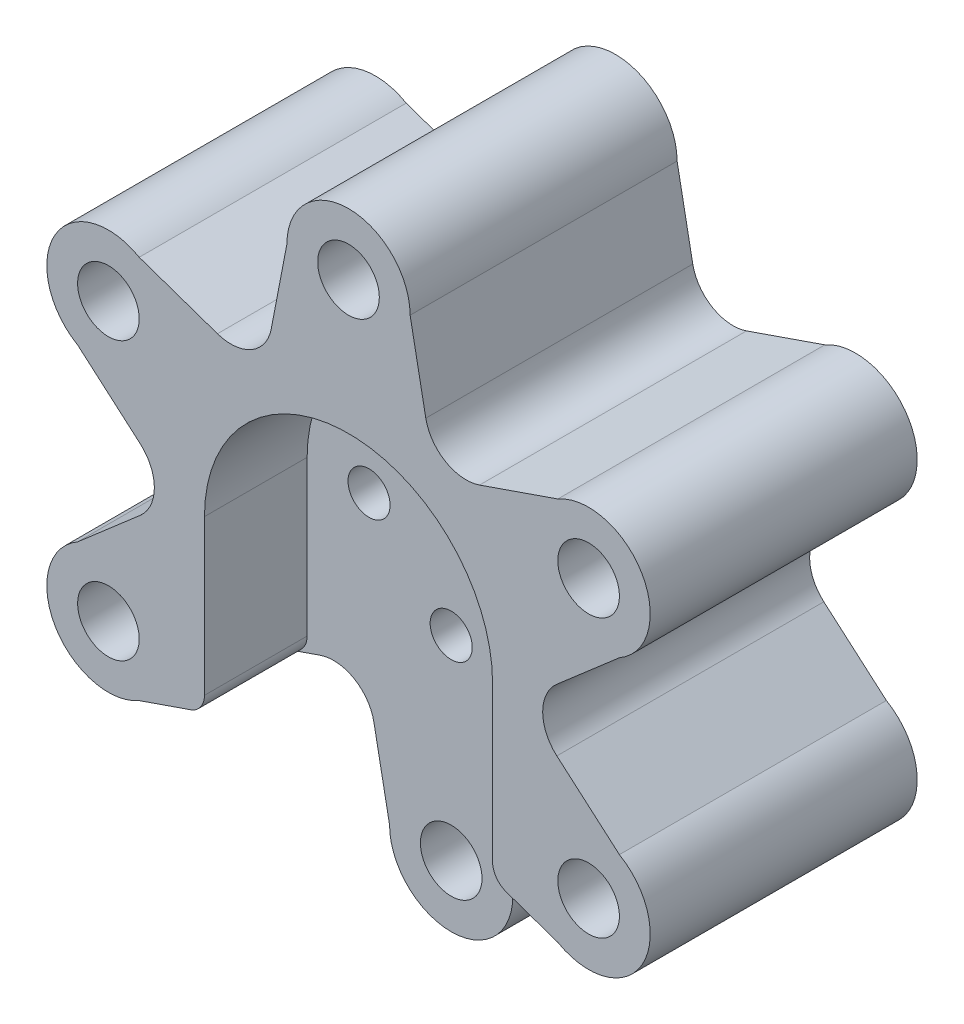
SolidWorks part; units mm, degrees
material "6061 合金"
ref_plane "前视基准面" through (0, 0, 0) normal (0, 0, 1) x (1, 0, 0)
ref_plane "上视基准面" through (0, 0, 0) normal (0, 1, 0) x (1, 0, 0)
ref_plane "右视基准面" through (0, 0, 0) normal (1, 0, 0) x (0, 0, -1)
sketch "草图2" plane through (0, 0, 0) normal (0, 0, 1) x (1, 0, 0)
  line L0 (0, 0) -> (0, 30) construction
  line L1 (-7.5425, 32.6667) -> (-16.9706, 6)
  line L2 (7.5425, 32.6667) -> (16.9706, 6)
  line L3 (-11.6913, -6.75) -> (0, 13.5) construction
  line L4 (0, 13.5) -> (11.6913, -6.75) construction
  line L5 (11.6913, -6.75) -> (-11.6913, -6.75) construction
  line L6 (0, 19.5) -> (-16.8875, -9.75) construction
  line L7 (-16.8875, -9.75) -> (16.8875, -9.75) construction
  line L8 (16.8875, -9.75) -> (0, 19.5) construction
  circle A0 centre (0, 0) radius 13.5 construction
  circle A1 centre (0, 13.5) radius 1.5
  circle A2 centre (11.6913, -6.75) radius 1.5
  circle A3 centre (-11.6913, -6.75) radius 1.5
  circle A4 centre (0, 0) radius 18 construction
  circle A5 centre (0, 30) radius 8
  circle A6 centre (0, 30) radius 2.5
  circle A7 centre (0, 0) radius 10.5
  circle A8 centre (0, -13.5) radius 1.5
  circle A9 centre (-11.6913, 6.75) radius 1.5
  circle A10 centre (11.6913, 6.75) radius 1.5
  circle A11 centre (0, 0) radius 18
  point P12 (0, 0)
  point P31 (0, 0)
  dimension "D1" = 27
  dimension "D2" = 3
  dimension "D4" = 36
  dimension "D6" = 16
  dimension "D8" = 5
  dimension "D10" = 3
  dimension "D12" = 36
  dimension "D13" = 3
  dimension "D5" = 30
  dimension "D7" = 3
  dimension "D9" = 3
  dimension "D3" = 3
  dimension "D11" = 3
extrude "凸台-拉伸1" add sketch "草图2" along normal blind 8 contours A11 A1 A2 A3 A7 A8 A9 A10
sketch "草图6" plane through (0, 0, 8) normal (0, 0, 1) x (1, 0, 0)
  circle A0 centre (0, 0) radius 10.5 construction
  circle A1 centre (0, 0) radius 10.5
extrude "凸台-拉伸2" add sketch "草图6" against normal blind 4
sketch "草图7" plane through (0, 0, 8) normal (0, 0, 1) x (1, 0, 0)
  line L0 (0, 0) -> (0, 20) construction
  line L1 (-7.5, 0) -> (-7.5, 20)
  line L2 (7.5, 0) -> (7.5, 20)
  arc A1 (-7.5, 0) -> (7.5, 0) centre (0, 0) ccw
  arc A2 (7.5, 20) -> (-7.5, 20) centre (0, 20) ccw
  circle A3 centre (0, 20) radius 3
  circle A4 centre (0, 0) radius 4 construction
  circle A5 centre (0, 4) radius 1.5
  circle A6 centre (4, 0) radius 1.5
  circle A7 centre (0, -4) radius 1.5
  circle A8 centre (-4, 0) radius 1.5
  point P3 (0, 10)
  point P24 (0, 0)
  dimension "D1" = 20
  dimension "D2" = 7.5
  dimension "D3" = 6
  dimension "D4" = 3
  dimension "D6" = 8
  dimension "D5" = 4
extrude "凸台-拉伸3" add sketch "草图7" along normal blind 4 separate body
sketch "草图9" plane through (0, 0, 8) normal (0, 0, 1) x (1, 0, 0)
  circle A0 centre (0, 4) radius 1.025
  circle A1 centre (-4, 0) radius 1.025
  circle A2 centre (0, -4) radius 1.025
  circle A3 centre (4, 0) radius 1.025
  dimension "D1" = 2.05
extrude "切除-拉伸2" cut sketch "草图9" against normal blind 4
sketch "草图11" plane through (0, 0, 12) normal (0, 0, 1) x (1, 0, 0)
  line L0 (-6.5, 20) -> (-7.5, 18.2679)
  line L1 (-7.5, 20) -> (-7.5, 0) construction
  line L2 (0, 20) -> (0, 0) construction
  line L3 (6.5, 20) -> (7.5, 18.2679)
  circle A0 centre (0, 20) radius 6.5
  line M7 (7.5, 0) -> (7.5, 20)
  arc M8 (7.5, 20) -> (-7.5, 20) centre (0, 20) ccw
  line M9 (-7.5, 20) -> (-7.5, 0)
  dimension "D1" = 13
  dimension "D2" = 30
extrude "切除-拉伸3" cut sketch "草图11" against normal blind 13 contours A0 L3 L0 M7 M8 M9
sketch "草图12" plane through (0, 0, 12) normal (0, 0, 1) x (1, 0, 0)
  line L0 (0, 20) -> (0, 0) construction
  line L1 (0, 12) -> (0, 10) construction
  line L2 (2.8, 12) -> (2.8, 10)
  line L3 (-2.8, 12) -> (-2.8, 10)
  arc A0 (2.8, 12) -> (-2.8, 12) centre (0, 12) ccw
  arc A1 (-2.8, 10) -> (2.8, 10) centre (0, 10) ccw
  point P6 (0, 11)
  dimension "D1" = 2.8
  dimension "D2" = 8
  dimension "D3" = 10
extrude "切除-拉伸4" cut sketch "草图12" against normal blind 23
sketch "草图13" plane through (0, 0, 8) normal (0, 0, 1) x (1, 0, 0)
  line L0 (0, 0) -> (0, 13.5) construction
  line L1 (-3, 13.5) -> (-4.2, 7.2746)
  line L2 (3, 13.5) -> (4.2, 7.2746)
  line L3 (10.1913, 9.3481) -> (4.2, 7.2746)
  line L4 (13.1913, 4.1519) -> (8.4, 0)
  line L5 (13.1913, -4.1519) -> (8.4, 0)
  line L6 (10.1913, -9.3481) -> (4.2, -7.2746)
  line L7 (3, -13.5) -> (4.2, -7.2746)
  line L8 (-3, -13.5) -> (-4.2, -7.2746)
  line L9 (-10.1913, -9.3481) -> (-4.2, -7.2746)
  line L10 (-13.1913, -4.1519) -> (-8.4, 0)
  line L11 (-13.1913, 4.1519) -> (-8.4, 0)
  line L12 (-10.1913, 9.3481) -> (-4.2, 7.2746)
  circle A0 centre (0, 13.5) radius 3
  circle A1 centre (11.6913, 6.75) radius 3
  circle A2 centre (11.6913, -6.75) radius 3
  circle A3 centre (0, -13.5) radius 3
  circle A4 centre (-11.6913, -6.75) radius 3
  circle A5 centre (-11.6913, 6.75) radius 3
  point P18 (0, 0)
  point P43 (0, 0)
  circle M13 centre (0, 0) radius 18
  dimension "D1" = 6
  dimension "D3" = 6
  dimension "D4" = 8.4
  dimension "D2" = 6
extrude "切除-拉伸5" cut sketch "草图13" against normal blind 8 contours A5 L12 L1 A0 L2 L3 A1 L4 L5 A2 L6 L7 A3 L8 L9 A4 L10 L11 M13
fillet "圆角6" radius 2 18 edges at (-8.4, 0, 6) (-10.3615, -1.6997, 2) (-6.6528, -8.1235, 2) (-4.2, -7.2746, 6) (-3.7087, -9.8232, 2) (3.7087, -9.8232, 2) (4.2, -7.2746, 6) (6.6528, -8.1235, 2) (10.3615, -1.6997, 2) (8.4, 0, 6) (10.3615, 1.6997, 2) (6.6528, 8.1235, 2) (4.2, 7.2746, 6) (3.7087, 9.8232, 2) (-4.2, 7.2746, 6) (-6.6528, 8.1235, 2) (-10.3615, 1.6997, 2) (-3.7087, 9.8232, 2)
sketch "草图15" plane through (0, 0, 12) normal (0, 0, 1) x (1, 0, 0)
  arc A1 (2.6872, 12.7869) -> (-2.6872, 12.7869) centre (0, 20) ccw
  arc A2 (2.8, 12) -> (-2.8, 12) centre (0, 12) ccw construction
  arc A3 (2.6872, 12.7869) -> (-2.6872, 12.7869) centre (0, 12) ccw
hole_wizard "M4 六角凹锥坑螺钉的锥形沉头孔2" positions "3D草图2" profile "草图20" countersink size "M4" standard "ISO"
sketch3d "3D草图2"
  circle A0 centre (0, 20, 8) radius 3 construction
  point P0 (0, 20, 8)
  point P5 (0, 20, 11)
sketch "草图20" plane through (0, 20, 8) normal (1, 0, 0) x (0, 1, 0)
  line L0 (0, 0) -> (0, 11.3519)
  line L1 (0, 11.3519) -> (2.25, 10)
  line L2 (2.25, 10) -> (2.25, 2.23)
  line L3 (2.25, 2.23) -> (4.48, 0)
  line L5 (4.48, 0) -> (0, 0)
  line L6 (-2.25, 2.23) -> (-4.48, 0) construction
  line L10 (0, 11.3519) -> (-2.25, 10) construction
  line L11 (0, -6.35) -> (0, 107.95) construction
  dimension "孔直径" = 4.5
  dimension "孔深度" = 10
  dimension "近端锥形沉头孔直径" = 8.96
  dimension "近端锥形沉头孔角度" = 90
  dimension "导头角度" = 118
fillet "圆角7" radius 2 4 edges at (-7.5, 18.2679, 10) (7.5, 18.2679, 10) (-6.5, 20, 10) (6.5, 20, 10)
sketch "草图21" plane through (0, 0, 0) normal (0, 0, -1) x (-1, 0, 0)
  circle A0 centre (0, 0) radius 16.5
  dimension "D1" = 33
sketch "草图22" plane through (0, 0, 12) normal (0, 0, 1) x (1, 0, 0)
  circle A0 centre (0, 0) radius 26.5
  dimension "D1" = 53
extrude "切除-拉伸7" cut sketch "草图22" against normal blind 4
sketch "草图23" plane through (0, 0, 8) normal (0, 0, 1) x (1, 0, 0)
  line L0 (7.015, 0) -> (7.015, -8.2488)
  line L2 (3, 13.5) -> (3.7632, 9.5409)
  line L3 (10.1913, -9.3481) -> (6.3811, -8.0294) construction
  line L4 (7, 0) -> (7, -20) construction
  line L5 (7.015, -8.2488) -> (10.1913, -9.3481)
  line L6 (13.1913, -4.1519) -> (10.1442, -1.5115)
  line L7 (11.454, 0) -> (9.454, 0) construction
  line L8 (7.015, 8.2488) -> (10.1913, 9.3481)
  line L9 (13.1913, 4.1519) -> (10.1442, 1.5115)
  line L10 (7.015, 8.2488) -> (6.3811, 8.0294)
  line L11 (10.1913, 9.3481) -> (6.3811, 8.0294) construction
  line L12 (0, 13.5) -> (0, 0) construction
  line L14 (0, 13.5) -> (0, 16.5) construction
  line L15 (-7.015, 0) -> (-7.015, -8.2488)
  line L16 (-7.015, -8.2488) -> (-10.1913, -9.3481)
  line L17 (-13.1913, -4.1519) -> (-10.1442, -1.5115)
  line L18 (-13.1913, 4.1519) -> (-10.1442, 1.5115)
  line L19 (-7.015, 8.2488) -> (-10.1913, 9.3481)
  line L20 (-7.015, 8.2488) -> (-6.3811, 8.0294)
  line L21 (-3, 13.5) -> (-3.7632, 9.5409)
  arc A0 (7.015, 0) -> (-7.015, 0) centre (0, 0) ccw
  circle A1 centre (11.6913, -6.75) radius 1.5
  arc A2 (10.1913, -9.3481) -> (13.1913, -4.1519) centre (11.6913, -6.75) ccw
  arc A3 (10.1442, 1.5115) -> (10.1442, -1.5115) centre (11.454, 0) ccw
  arc A4 (10.1913, 9.3481) -> (13.1913, 4.1519) centre (11.6913, 6.75) cw
  circle A5 centre (11.6913, 6.75) radius 1.5
  arc A6 (3.7632, 9.5409) -> (6.3811, 8.0294) centre (5.727, 9.9195) ccw
  circle A7 centre (0, 13.5) radius 1.5
  arc A8 (3, 13.5) -> (-3, 13.5) centre (0, 13.5) ccw
  circle A10 centre (-11.6913, -6.75) radius 1.5
  arc A11 (-10.1913, -9.3481) -> (-13.1913, -4.1519) centre (-11.6913, -6.75) cw
  arc A12 (-10.1442, 1.5115) -> (-10.1442, -1.5115) centre (-11.454, 0) cw
  circle A13 centre (-11.6913, 6.75) radius 1.5
  arc A14 (-10.1913, 9.3481) -> (-13.1913, 4.1519) centre (-11.6913, 6.75) ccw
  arc A15 (-3.7632, 9.5409) -> (-6.3811, 8.0294) centre (-5.727, 9.9195) cw
  dimension "D1" = 14.03
  dimension "D2" = 3
  dimension "D3" = 4
  dimension "D4" = 3
extrude "凸台-拉伸4" add sketch "草图23" along normal blind 5
fillet "圆角8" radius 1 2 edges at (7.015, -8.2488, 10.5) (-7.015, -8.2488, 10.5)
sketch "草图24" plane through (0, 0, 4) normal (0, 0, -1) x (-1, 0, 0)
  line L0 (-3.7632, 9.5409) -> (-3.1303, 12.824)
  line L1 (-3.1303, 12.824) -> (-3.7632, 9.5409) construction
  line L2 (3.7632, 9.5409) -> (3.1303, 12.824)
  line L3 (3.1303, 12.824) -> (3.7632, 9.5409) construction
  line L4 (6.3811, 8.0294) -> (9.5408, 9.1229)
  line L5 (10.1442, 1.5115) -> (12.6711, 3.7011)
  line L6 (10.1442, -1.5115) -> (12.6711, -3.7011)
  line L7 (6.3811, -8.0294) -> (9.5408, -9.1229)
  line L8 (3.7632, -9.5409) -> (3.1303, -12.824)
  line L9 (-3.7632, -9.5409) -> (-3.1303, -12.824)
  line L10 (-6.3811, -8.0294) -> (-9.5408, -9.1229)
  line L11 (-10.1442, -1.5115) -> (-12.6711, -3.7011)
  line L12 (-10.1442, 1.5115) -> (-12.6711, 3.7011)
  line L13 (-6.3811, 8.0294) -> (-9.5408, 9.1229)
  arc A1 (0.9798, 10.4542) -> (3.1303, 12.824) centre (1.1665, 12.4455) ccw
  arc A2 (-3.1303, 12.824) -> (-0.9798, 10.4542) centre (-1.1665, 12.4455) ccw
  arc A3 (-6.3811, 8.0294) -> (-3.7632, 9.5409) centre (-5.727, 9.9195) ccw
  arc A4 (-6.3811, 8.0294) -> (-3.7632, 9.5409) centre (-5.727, 9.9195) ccw construction
  arc A5 (0.9798, 10.4542) -> (-0.9798, 10.4542) centre (0, 0) ccw
  arc A6 (0.9798, 10.4542) -> (-0.9798, 10.4542) centre (0, 0) ccw construction
  arc A7 (3.7632, 9.5409) -> (6.3811, 8.0294) centre (5.727, 9.9195) ccw
  arc A8 (9.5408, 9.1229) -> (8.5637, 6.0756) centre (10.1949, 7.2329) ccw
  arc A9 (9.5435, 4.3785) -> (8.5637, 6.0756) centre (0, 0) ccw
  arc A10 (9.5435, 4.3785) -> (12.6711, 3.7011) centre (11.3613, 5.2125) ccw
  arc A11 (10.1442, 1.5115) -> (10.1442, -1.5115) centre (11.454, 0) ccw
  arc A12 (12.6711, -3.7011) -> (9.5435, -4.3785) centre (11.3613, -5.2125) ccw
  arc A13 (8.5637, -6.0756) -> (9.5435, -4.3785) centre (0, 0) ccw
  arc A14 (8.5637, -6.0756) -> (9.5408, -9.1229) centre (10.1949, -7.2329) ccw
  arc A15 (6.3811, -8.0294) -> (3.7632, -9.5409) centre (5.727, -9.9195) ccw
  arc A16 (3.1303, -12.824) -> (0.9798, -10.4542) centre (1.1665, -12.4455) ccw
  arc A17 (-0.9798, -10.4542) -> (0.9798, -10.4542) centre (0, 0) ccw
  arc A18 (-0.9798, -10.4542) -> (-3.1303, -12.824) centre (-1.1665, -12.4455) ccw
  arc A19 (-3.7632, -9.5409) -> (-6.3811, -8.0294) centre (-5.727, -9.9195) ccw
  arc A20 (-9.5408, -9.1229) -> (-8.5637, -6.0756) centre (-10.1949, -7.2329) ccw
  arc A21 (-9.5435, -4.3785) -> (-8.5637, -6.0756) centre (0, 0) ccw
  arc A22 (-9.5435, -4.3785) -> (-12.6711, -3.7011) centre (-11.3613, -5.2125) ccw
  arc A23 (-10.1442, -1.5115) -> (-10.1442, 1.5115) centre (-11.454, 0) ccw
  arc A24 (-12.6711, 3.7011) -> (-9.5435, 4.3785) centre (-11.3613, 5.2125) ccw
  arc A25 (-8.5637, 6.0756) -> (-9.5435, 4.3785) centre (0, 0) ccw
  arc A26 (-8.5637, 6.0756) -> (-9.5408, 9.1229) centre (-10.1949, 7.2329) ccw
  circle A27 centre (-4, 0) radius 1.025
  circle A28 centre (0, 4) radius 1.025
  circle A29 centre (4, 0) radius 1.025
  circle A30 centre (0, -4) radius 1.025
  point P78 (0, 0)
  dimension "D1" = 2
  dimension "D3" = 2.05
  dimension "D2" = 6
extrude "凸台-拉伸5" add sketch "草图24" along normal blind 4
